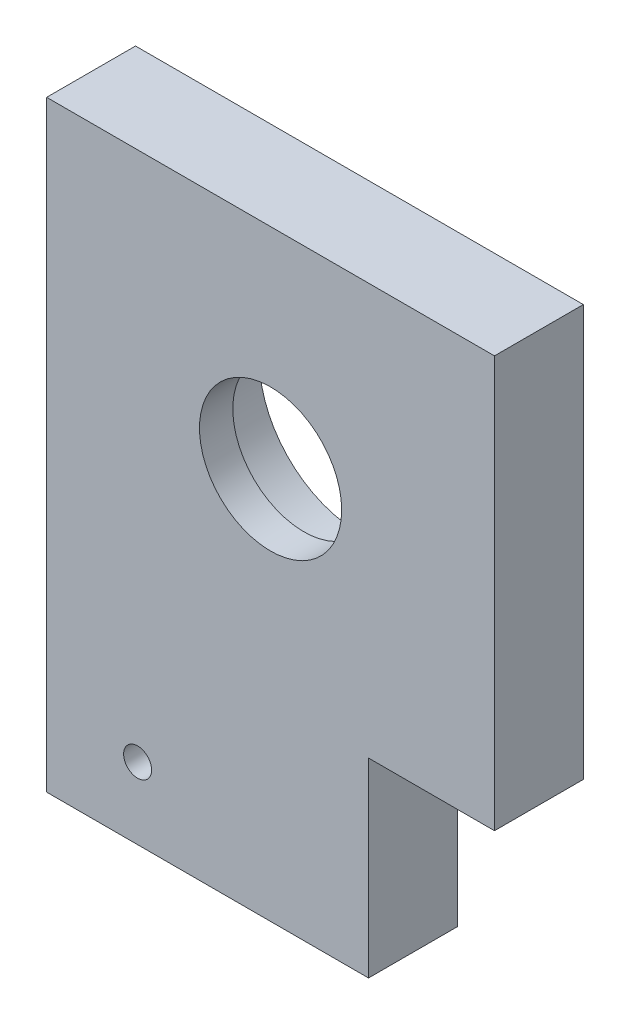
SolidWorks part; units mm, degrees
material "Plain Carbon Steel"
ref_plane "Front Plane" through (0, 0, 0) normal (0, 0, 1) x (1, 0, 0)
ref_plane "Top Plane" through (0, 0, 0) normal (0, 1, 0) x (1, 0, 0)
ref_plane "Right Plane" through (0, 0, 0) normal (1, 0, 0) x (0, 0, -1)
sketch "Sketch1" plane through (0, 0, 0) normal (0, 0, 1) x (1, 0, 0)
  line L1 (14, -56) -> (-32, -56)
  line L2 (-32, -56) -> (-32, 0)
  line L3 (0, 0) -> (0, -56) construction
  line L4 (-32, 0) -> (32, 0) construction
  line L5 (14, -56) -> (14, -28.775)
  line L6 (14, -28.775) -> (32, -28.775)
  line L7 (32, -28.775) -> (32, 30)
  line L8 (32, 30) -> (-32, 30)
  line L9 (-32, 30) -> (-32, 0)
  circle A0 centre (0, 0) radius 14.2875 construction
  circle A4 centre (0, 0) radius 10.16
  circle A5 centre (-19, -45.775) radius 2
  dimension "D1" = 32
  dimension "D2" = 46
  dimension "D6" = 20.32
  dimension "D9" = 4
  dimension "D3" = 56
  dimension "D4" = 30
  dimension "D5" = 27.225
  dimension "D7" = 13
  dimension "D8" = 17
extrude "Boss-Extrude1" add sketch "Sketch1" along normal blind 12.7
sketch "Sketch2" plane through (0, 0, 0) normal (0, 0, 1) x (1, 0, 0)
  circle A0 centre (0, 0) radius 14.2875
  dimension "D1" = 28.575
extrude "Cut-Extrude1" cut sketch "Sketch2" along normal blind 7.9375 from surface at 0 starting at face at (4.6667, -18.2583, 0)
